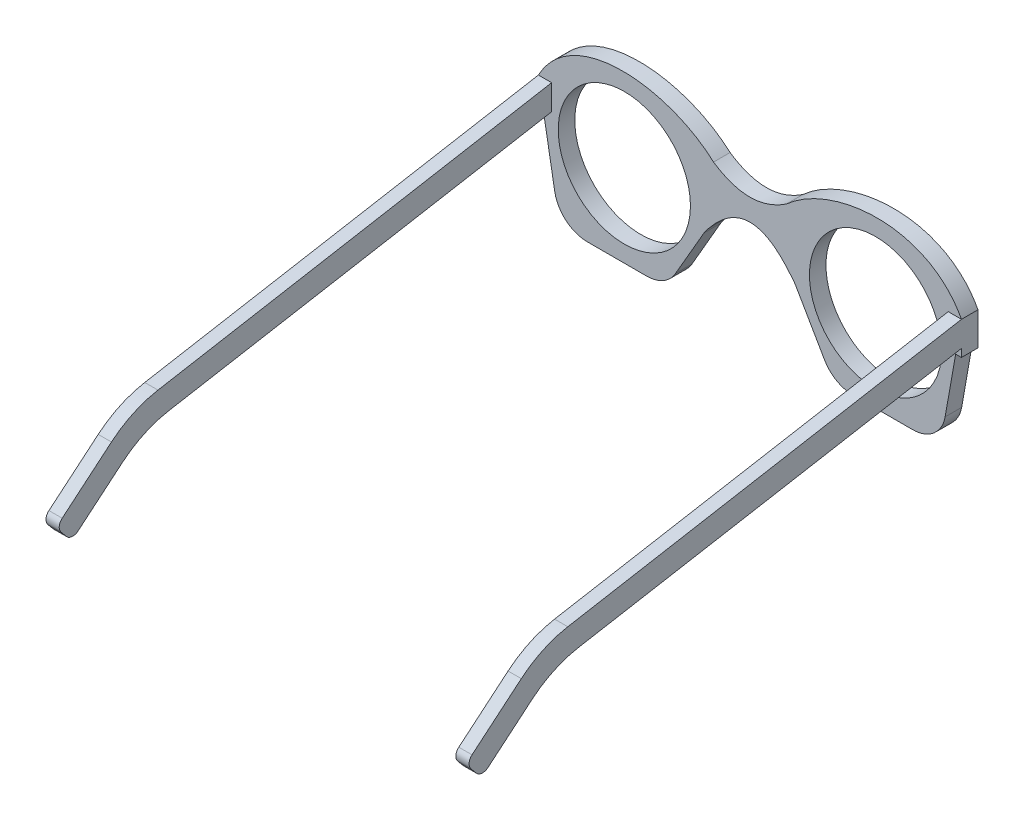
SolidWorks part; units mm, degrees
ref_plane "Front Plane" through (0, 0, 0) normal (0, 0, 1) x (1, 0, 0)
ref_plane "Top Plane" through (0, 0, 0) normal (0, 1, 0) x (1, 0, 0)
ref_plane "Right Plane" through (0, 0, 0) normal (1, 0, 0) x (0, 0, -1)
sketch "Sketch1" plane through (0, 0, 0) normal (0, 0, 1) x (1, 0, 0)
  line L0 (0, 53.9694) -> (0, -68.1219) construction
  line L1 (64, 20.6092) -> (59.0553, -7.4334)
  line L2 (49.2073, -15.6969) -> (31.2073, -15.6969)
  line L3 (22.547, -10.6969) -> (13.8868, 4.3031)
  line L4 (5.2265, 9.3031) -> (-5.2265, 9.3031)
  line L5 (-11, 24.3031) -> (11, 24.3031)
  line L6 (-22.547, -10.6969) -> (-13.8868, 4.3031)
  line L7 (-49.2073, -15.6969) -> (-31.2073, -15.6969)
  line L8 (-64, 20.6092) -> (-59.0553, -7.4334)
  line L9 (-64, 20.6092) -> (-64, 10.6092)
  line L10 (-64, 10.6092) -> (-62.2367, 10.6092)
  line L11 (64, 20.6092) -> (64, 10.6092)
  line L12 (64, 10.6092) -> (62.2367, 10.6092)
  circle A1 centre (38, 9.3031) radius 20
  arc A2 (22.547, -10.6969) -> (31.2073, -15.6969) centre (31.2073, -5.6969) ccw
  arc A3 (49.2073, -15.6969) -> (59.0553, -7.4334) centre (49.2073, -5.6969) ccw
  arc A4 (13.8868, 4.3031) -> (5.2265, 9.3031) centre (5.2265, -0.6969) ccw
  arc A5 (-13.8868, 4.3031) -> (-5.2265, 9.3031) centre (-5.2265, -0.6969) cw
  arc A6 (-49.2073, -15.6969) -> (-59.0553, -7.4334) centre (-49.2073, -5.6969) cw
  arc A7 (-22.547, -10.6969) -> (-31.2073, -15.6969) centre (-31.2073, -5.6969) cw
  circle A8 centre (-38, 9.3031) radius 20
  spline S0 degree 3 poles (11, 24.3031) (25.026, 37.0348) (53.8058, 39.7507) (64, 20.6092) knots 0 0 0 0 1 1 1 1
  spline S1 degree 3 poles (-11, 24.3031) (-25.026, 37.0348) (-53.8058, 39.7507) (-64, 20.6092) knots 0 0 0 0 1 1 1 1
  spline S2 degree 2 poles (11, 24.3031) (0, 16.9153) (-11, 24.3031) knots 0 0 0 1 1 1
  spline S3 degree 2 poles (-13.8868, 4.3031) (0, 23.7912) (13.8868, 4.3031) knots 0 0 0 1 1 1
  point P8 (0, 9.3031)
  point P10 (-11, 9.3031)
  point P21 (11, 9.3031)
  point P38 (0, 24.3031)
  dimension "D1" = 40
  dimension "D2" = 11
  dimension "D8" = 10
  dimension "D5" = 10
  dimension "D3" = 38
  dimension "D4" = 11
  dimension "D6" = 0
  dimension "D7" = 15
  dimension "D9" = 64
  dimension "D10" = 40
  dimension "D11" = 100
  dimension "D12" = 120
  dimension "D13" = 18
  dimension "D14" = 10
extrude "Boss-Extrude1" add sketch "Sketch1" along normal blind 5 contours L0 S2 S1 L8 A6 L7 A7 L6 A5 S3 A8 | S2 L0 S3 A4 L3 A2 L2 A3 L1 S0 A1 | L12 L11 L1 | L9 L10 L8
sketch "Sketch3" plane through (-64, 0, 0) normal (-1, 0, 0) x (0, 0, 1)
  line L0 (5, 20.6092) -> (124.1023, -0.3917)
  line L2 (138.1765, -6.9546) -> (153.0849, -19.4643)
  line L3 (153.393, -22.9863) -> (151.7861, -24.9015)
  line L4 (148.264, -25.2096) -> (134.895, -13.9917)
  line L5 (120.8209, -7.4288) -> (5, 12.9935)
  line L7 (5, 20.6092) -> (0, 20.6092) construction
  line L8 (5, 20.6092) -> (5, 10.6092) construction
  line L9 (5, -15.6969) -> (83.2041, -15.6969) construction
  line L12 (0, 20.6092) -> (0, 10.6092)
  line L13 (0, 10.6092) -> (5, 10.6092)
  line L14 (5, 10.6092) -> (5, 20.6092)
  line L15 (5, 20.6092) -> (0, 20.6092)
  line L16 (0, 20.6092) -> (0, 10.6092)
  line L17 (0, 10.6092) -> (5, 10.6092)
  line L18 (5, 10.6092) -> (5, 12.9935)
  line L19 (5, 20.6092) -> (0, 20.6092)
  arc A0 (134.895, -13.9917) -> (120.8209, -7.4288) centre (115.6114, -36.9731) ccw
  arc A1 (138.1765, -6.9546) -> (124.1023, -0.3917) centre (118.8929, -29.936) ccw
  arc A2 (153.393, -22.9863) -> (153.0849, -19.4643) centre (151.4779, -21.3794) ccw
  arc A3 (151.7861, -24.9015) -> (148.264, -25.2096) centre (149.871, -23.2945) cw
  point P2 (0, 0)
  point P19 (132.0187, -1.7876)
  point P22 (155, -21.0712)
  dimension "D7" = 30
  dimension "D8" = 2.5
  dimension "D1" = 190
  dimension "D2" = 7.5
  dimension "D3" = 7.5
  dimension "D4" = 30
  dimension "D5" = 150
  dimension "D6" = 30
  dimension "D9" = 0
extrude "Boss-Extrude2" add sketch "Sketch3" against normal blind 4
mirror "Mirror1" about plane through (0, 0, 0) normal (1, 0, 0) of "Boss-Extrude2"
